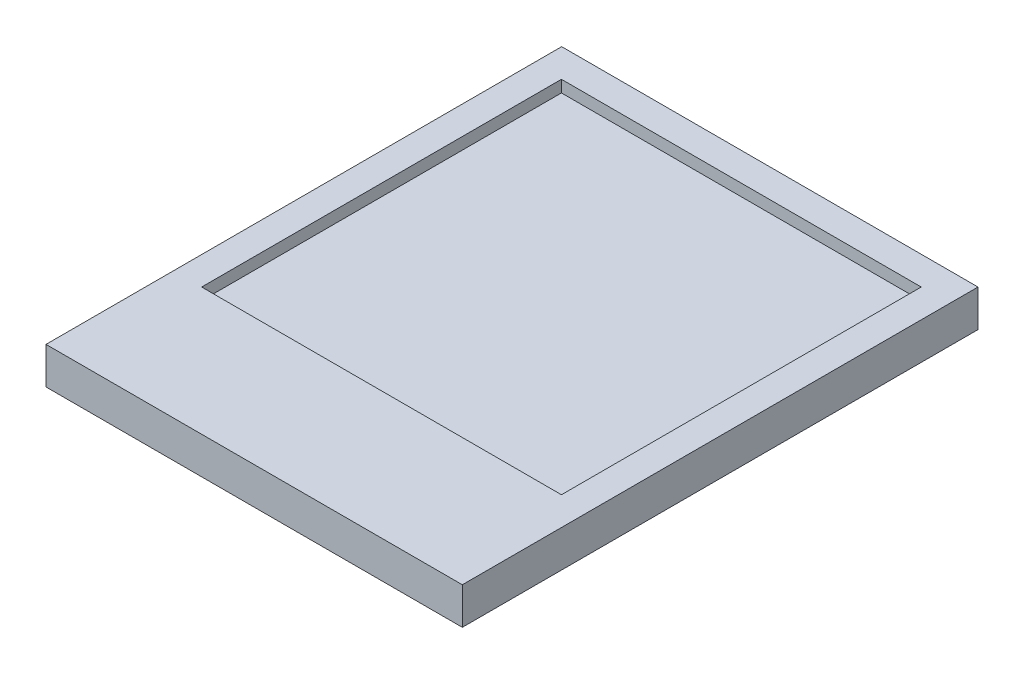
SolidWorks part; units mm, degrees
ref_plane "前视基准面" through (0, 0, 0) normal (0, 0, 1) x (1, 0, 0)
ref_plane "上视基准面" through (0, 0, 0) normal (0, 1, 0) x (1, 0, 0)
ref_plane "右视基准面" through (0, 0, 0) normal (1, 0, 0) x (0, 0, -1)
sketch "草图1" plane through (0, 0, 0) normal (0, 1, 0) x (1, 0, 0)
  line L1 (-7.8276, 6.7094) -> (9.7724, 6.7094)
  line L2 (-7.8276, 6.7094) -> (-7.8276, -15.0906)
  line L3 (-7.8276, -15.0906) -> (9.7724, -15.0906)
  line L4 (9.7724, 6.7094) -> (9.7724, -15.0906)
  dimension "D1" = 17.6
  dimension "D2" = 21.8
extrude "凸台-拉伸1" add sketch "草图1" along normal blind 1.56
sketch "草图2" plane through (0, 1.56, 0) normal (0, 1, 0) x (1, 0, 0)
  line L0 (9.7724, -15.0906) -> (9.7724, 6.7094) construction
  line L5 (-6.6376, 5.5094) -> (8.5724, 5.5094)
  line L6 (-6.6376, 5.5094) -> (-6.6376, -9.7006)
  line L7 (-6.6376, -9.7006) -> (8.5724, -9.7006)
  line L8 (8.5724, 5.5094) -> (8.5724, -9.7006)
  line L9 (9.7724, 6.7094) -> (-7.8276, 6.7094) construction
  dimension "D1" = 15.21
  dimension "D2" = 15.21
  dimension "D3" = 1.2
  dimension "D4" = 1.2
extrude "切除-拉伸1" cut sketch "草图2" against normal blind 0.5
